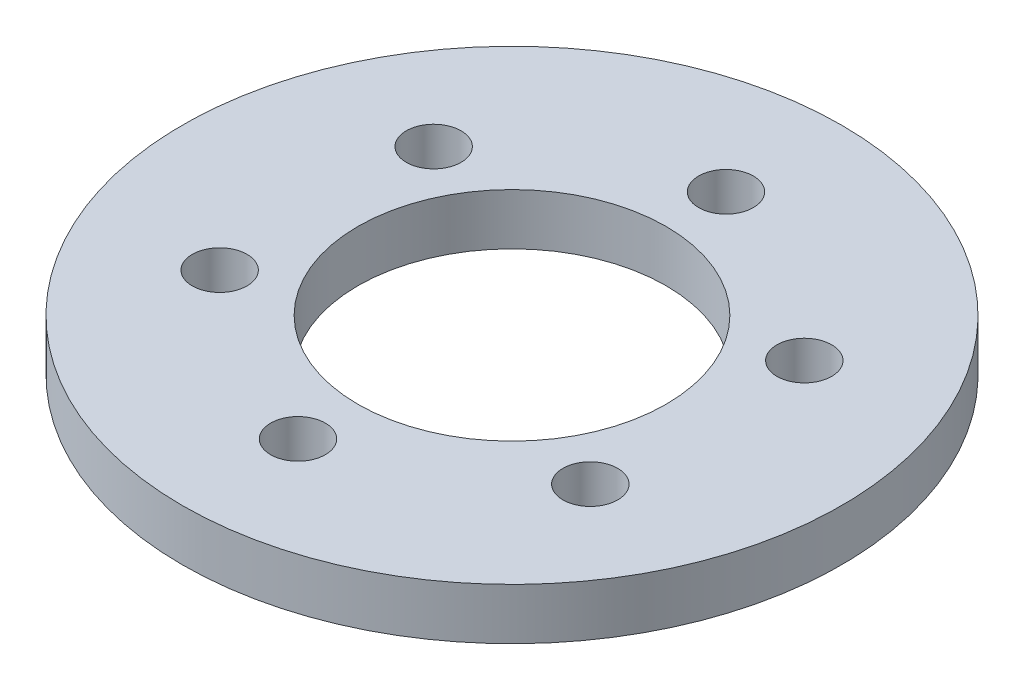
SolidWorks part; units mm, degrees
material "Thornel Mat VMA"
ref_plane "Front Plane" through (0, 0, 0) normal (0, 0, 1) x (1, 0, 0)
ref_plane "Top Plane" through (0, 0, 0) normal (0, 1, 0) x (1, 0, 0)
ref_plane "Right Plane" through (0, 0, 0) normal (1, 0, 0) x (0, 0, -1)
sketch "Sketch1" plane through (0, 0, 0) normal (0, 1, 0) x (1, 0, 0)
  line L0 (0, 0) -> (0, 12.5) construction
  circle A0 centre (0, 0) radius 19.25
  circle A1 centre (0, 0) radius 9
  circle A2 centre (0, 12.5) radius 1.6
  circle A3 centre (10.8253, 6.25) radius 1.6
  circle A4 centre (10.8253, -6.25) radius 1.6
  circle A5 centre (0, -12.5) radius 1.6
  circle A6 centre (-10.8253, -6.25) radius 1.6
  circle A7 centre (-10.8253, 6.25) radius 1.6
  point P7 (-11.774, 8.8016)
  point P8 (0, 0)
  point P18 (0, 0)
  dimension "D1" = 38.5
  dimension "D2" = 18
  dimension "D4" = 3.2
  dimension "D3" = 12.5
  dimension "D5" = 6
extrude "Boss-Extrude1" add sketch "Sketch1" along normal blind 3
